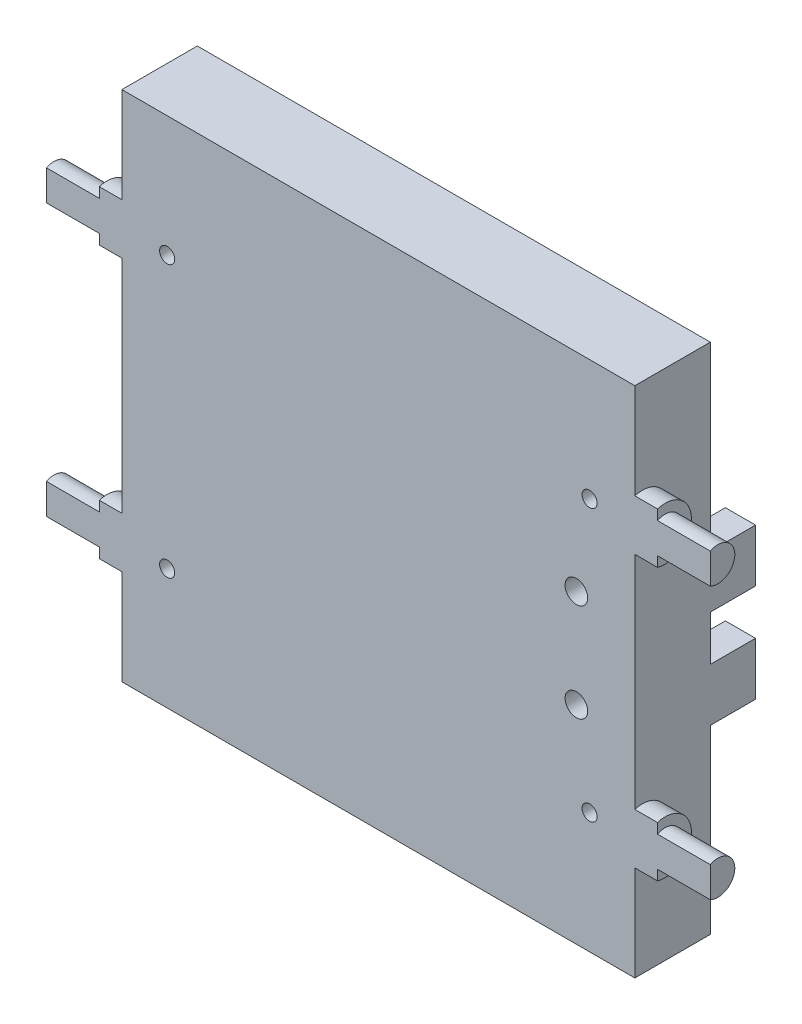
SolidWorks part; units mm, degrees
ref_plane "Front Plane" through (0, 0, 0) normal (0, 0, 1) x (1, 0, 0)
ref_plane "Top Plane" through (0, 0, 0) normal (0, 1, 0) x (1, 0, 0)
ref_plane "Right Plane" through (0, 0, 0) normal (1, 0, 0) x (0, 0, -1)
sketch "Sketch1" plane through (0, 0, 0) normal (0, 0, 1) x (1, 0, 0)
  line L1 (0, 0) -> (-68, 0)
  line L2 (0, 0) -> (0, -68)
  line L3 (0, -68) -> (-68, -68)
  line L4 (-68, 0) -> (-68, -68)
  dimension "D1" = 68
  dimension "D2" = 68
extrude "Boss-Extrude1" add sketch "Sketch1" along normal blind 10
sketch "Sketch2" plane through (-68, 0, 0) normal (-1, 0, 0) x (0, 0, 1)
  line L1 (10, 0) -> (0, 0) construction
  line L2 (10, -68) -> (0, -68) construction
  line L3 (10, 0) -> (10, -68) construction
  line L4 (10, 0) -> (10, -68)
  circle A0 centre (9, -52) radius 3.5
  circle A1 centre (9, -16) radius 3.5
  dimension "D1" = 7
  dimension "D2" = 7
  dimension "D3" = 1
  dimension "D4" = 0
  dimension "D5" = 16
  dimension "D6" = 16
extrude "Boss-Extrude2" add sketch "Sketch2" along normal blind 3 contours L4 A1 | L4 A0
sketch "Sketch3" plane through (-71, 0, 0) normal (-1, 0, 0) x (0, 0, 1)
  line L0 (10, -55.3541) -> (10, -12.6459)
  circle A0 centre (9, -52) radius 2.25
  circle A1 centre (9, -16) radius 2.25
  dimension "D1" = 4.5
  dimension "D2" = 4.5
extrude "Boss-Extrude3" add sketch "Sketch3" along normal blind 7 contours L0 A0 | L0 A1
sketch "Sketch4" plane through (0, 0, 0) normal (1, 0, 0) x (0, 0, -1)
  line L0 (-10, 0) -> (0, 0) construction
  line L1 (-10, -68) -> (0, -68) construction
  line L2 (-10, 0) -> (-10, -68)
  circle A0 centre (-9, -16) radius 3.5
  circle A1 centre (-9, -52) radius 3.5
  dimension "D1" = 16
  dimension "D2" = 16
  dimension "D3" = 7
  dimension "D4" = 7
  dimension "D5" = 1
  dimension "D6" = 0
extrude "Boss-Extrude4" add sketch "Sketch4" along normal blind 3 contours L2 A0 | L2 A1
sketch "Sketch5" plane through (3, 0, 0) normal (1, 0, 0) x (0, 0, -1)
  line L0 (-10, -12.6459) -> (-10, -55.3541)
  circle A0 centre (-9, -16) radius 2.25
  circle A1 centre (-9, -52) radius 2.25
  dimension "D1" = 4.5
  dimension "D2" = 4.5
extrude "Boss-Extrude5" add sketch "Sketch5" along normal blind 7 contours L0 A0 | L0 A1
sketch "Sketch6" plane through (0, 0, 0) normal (0, 0, -1) x (-1, 0, 0)
  line L0 (0, -34) -> (68, -34) construction
  line L1 (55.25, -12.75) -> (12.75, -12.75)
  line L2 (55.25, -12.75) -> (55.25, -55.25)
  line L3 (55.25, -55.25) -> (12.75, -55.25)
  line L4 (12.75, -12.75) -> (12.75, -55.25)
  line L5 (0, -68) -> (0, 0) construction
  line L6 (68, 0) -> (68, -68) construction
  line L7 (34, 0) -> (34, -68) construction
  line L8 (0, 0) -> (68, 0) construction
  line L9 (68, -68) -> (0, -68) construction
  point P16 (12.75, -34)
  point P17 (34, -55.25)
  dimension "D1" = 42.5
  dimension "D2" = 42.5
  dimension "D3" = 0
  dimension "D4" = 0
extrude "Cut-Extrude1" cut sketch "Sketch6" against normal blind 3
sketch "Sketch8" plane through (0, 0, 0) normal (0, 0, -1) x (-1, 0, 0)
  line L0 (55.25, -12.75) -> (12.75, -12.75) construction
  line L2 (12.75, -12.75) -> (12.75, -55.25) construction
  line L3 (34, 0) -> (34, -108.8236) construction
  line L4 (0, 0) -> (68, 0) construction
  line L5 (0, -34) -> (112.3527, -34) construction
  line L6 (0, -68) -> (0, 0) construction
  circle A0 centre (20.75, -7.75) radius 1.5
  circle A3 centre (47.25, -7.75) radius 1.5
  circle A4 centre (47.25, -60.25) radius 1.5
  circle A5 centre (20.75, -60.25) radius 1.5
  dimension "D1" = 5
  dimension "D3" = 3
  dimension "D5" = 8
extrude "Cut-Extrude2" cut sketch "Sketch8" against normal blind 5
sketch "Sketch9" plane through (0, 0, 0) normal (0, 0, -1) x (-1, 0, 0)
  line L1 (0, -24) -> (4, -24)
  line L2 (0, -24) -> (0, -31)
  line L3 (0, -31) -> (4, -31)
  line L4 (4, -24) -> (4, -31)
  line L5 (0, -68) -> (0, 0) construction
  line L6 (0, -34) -> (68, -34) construction
  line L7 (68, 0) -> (68, -68) construction
  line L8 (0, -37) -> (4, -37)
  line L9 (4, -44) -> (4, -37)
  line L10 (0, -44) -> (4, -44)
  line L11 (0, -44) -> (0, -37)
  point P6 (0, -34)
  dimension "D1" = 4
  dimension "D2" = 7
  dimension "D3" = 0
  dimension "D4" = 3
extrude "Boss-Extrude6" add sketch "Sketch9" along normal blind 6
sketch "Sketch10" plane through (0, 0, 0) normal (0, 0, -1) x (-1, 0, 0)
  line L0 (0, -34) -> (23.3312, -34) construction
  line L1 (0, -37) -> (0, -31) construction
  line L2 (12.75, -12.75) -> (12.75, -55.25) construction
  line L3 (4, -31) -> (4, -24) construction
  circle A0 centre (7.75, -27.5) radius 1.5
  circle A1 centre (7.75, -40.5) radius 1.5
  point P10 (4, -27.5)
  dimension "D1" = 3
  dimension "D2" = 5
  dimension "D3" = 0
extrude "Cut-Extrude3" cut sketch "Sketch10" against normal blind 10
sketch "Sketch11" plane through (0, 0, 10) normal (0, 0, 1) x (1, 0, 0)
  line L0 (-68, -34) -> (19.7059, -34) construction
  line L1 (-68, -19.3541) -> (-68, -48.6459) construction
  line L2 (-34, -68) -> (-34, 32.0149) construction
  line L3 (-68, -68) -> (0, -68) construction
  line L4 (-78, -54.0156) -> (-78, -49.9844) construction
  circle A0 centre (-62, -52) radius 1
  circle A1 centre (-62, -16) radius 1
  circle A2 centre (-6, -52) radius 1
  circle A3 centre (-6, -16) radius 1
  point P12 (-78, -52)
  dimension "D1" = 16
  dimension "D2" = 0
  dimension "D3" = 2
extrude "Cut-Extrude4" cut sketch "Sketch11" against normal blind 20
sketch "Sketch13" plane through (0, 0, 0) normal (0, 0, -1) x (-1, 0, 0)
  line L0 (68, 0) -> (68, -68) construction
  line L1 (58.5, -26) -> (65.5, -26)
  line L2 (58.5, -26) -> (58.5, -42)
  line L3 (58.5, -42) -> (65.5, -42)
  line L4 (65.5, -26) -> (65.5, -42)
  circle A0 centre (62, -16) radius 1 construction
  point P4 (65.5, -34)
  point P7 (68, -34)
  point P8 (62, -26)
  dimension "D1" = 7
  dimension "D2" = 0
  dimension "D3" = 16
  dimension "D4" = 0
extrude "Boss-Extrude7" add sketch "Sketch13" along normal blind 12
sketch "Sketch15" plane through (-65.5, 0, 0) normal (-1, 0, 0) x (0, 0, 1)
  line L0 (-12, -34) -> (24.0661, -34) construction
  line L1 (-12, -42) -> (-12, -26) construction
  line L2 (-12, -32) -> (-3, -32)
  line L3 (-3, -32) -> (-5, -30)
  line L4 (-5, -30) -> (-12, -30)
  line L5 (-12, -30) -> (-12, -32)
  line L6 (-12, -26) -> (0, -26) construction
  line L7 (-12, -38) -> (-12, -36)
  line L8 (-3, -36) -> (-5, -38)
  line L9 (-5, -38) -> (-12, -38)
  line L10 (-12, -36) -> (-3, -36)
  dimension "D1" = 2
  dimension "D2" = 4
  dimension "D3" = 45
  dimension "D4" = 7
extrude "Cut-Extrude5" cut sketch "Sketch15" against normal blind 10
sketch "Sketch16" plane through (-65.5, 0, 0) normal (-1, 0, 0) x (0, 0, 1)
  line L0 (0, -26) -> (-12, -26)
  line L1 (-12, -26) -> (0, -21)
  line L2 (0, -21) -> (0, -26)
  line L3 (-12, -34) -> (21.219, -34) construction
  line L4 (-12, -36) -> (-12, -32) construction
  line L5 (-12, -42) -> (0, -47)
  line L6 (0, -42) -> (-12, -42)
  line L7 (0, -47) -> (0, -42)
  dimension "D1" = 5
extrude "Boss-Extrude8" add sketch "Sketch16" against normal up to vertex
